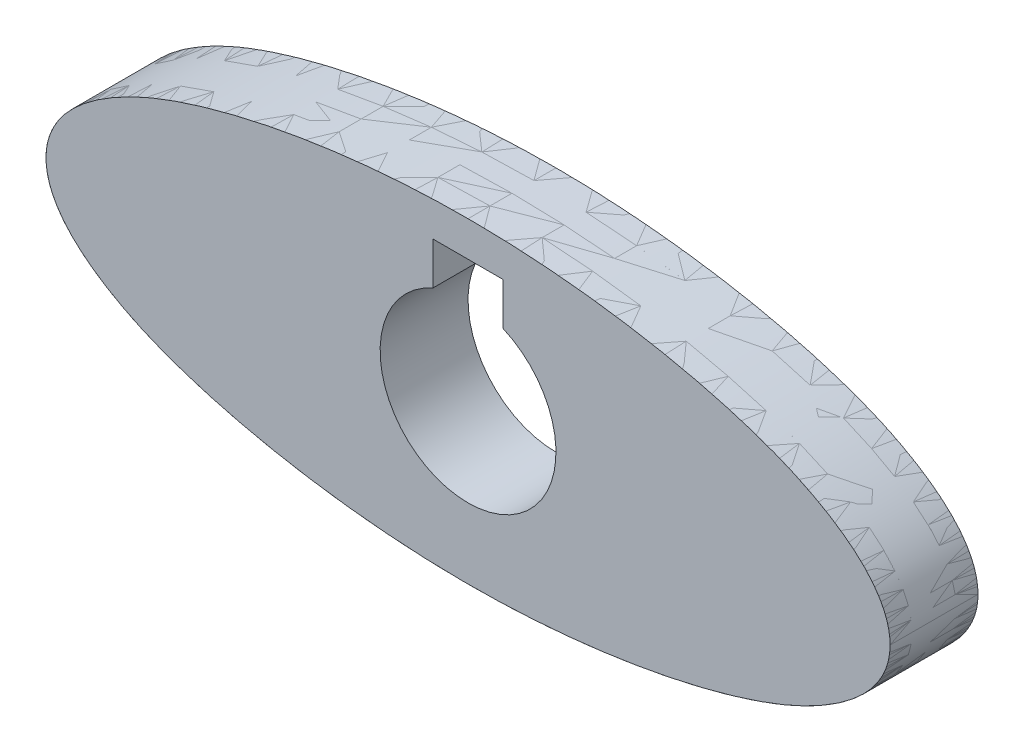
SolidWorks part; units mm, degrees
ref_plane "Alzado" through (0, 0, 0) normal (0, 0, 1) x (1, 0, 0)
ref_plane "Planta" through (0, 0, 0) normal (0, 1, 0) x (1, 0, 0)
ref_plane "Vista lateral" through (0, 0, 0) normal (1, 0, 0) x (0, 0, -1)
ref_plane "Plano1" through (0, 0, 0) normal (0, 0, -1) x (-1, 0, 0)
sketch "Croquis1" plane through (0, 0, 0) normal (0, 0, -1) x (-1, 0, 0)
  circle A0 centre (0, 0) radius 5
  spline S0 degree 3 poles (24, 0) (24, 1.5) (23.04, 3.48) (15.36, 7.32) (8, 9) (-8, 9) (-15.36, 7.32) (-23.04, 3.48) (-24, 1.5) (-24, 0) knots 0 0 0 0 0.25 0.25 0.5 0.5 0.75 0.75 1 1 1 1
  spline S1 degree 3 poles (-24, 0) (-24, -1.5) (-23.04, -3.48) (-15.36, -7.32) (-8, -9) (8, -9) (15.36, -7.32) (23.04, -3.48) (24, -1.5) (24, 0) knots 0 0 0 0 0.25 0.25 0.5 0.5 0.75 0.75 1 1 1 1
extrude "Saliente-Extruir1" add sketch "Croquis1" against normal blind 5
sketch "Croquis2" plane through (0, 0, 5) normal (0, 0, 1) x (1, 0, 0)
  spline S0 degree 3 poles (2832.0202, -1053.5368) (-359.2346, 53.9786) (68.6348, 19.3174) (15.36, -7.32) (8, -9) (-8, -9) (-15.36, -7.32) (-68.6347, 19.3174) (359.2335, 53.9785) (-2832.0071, -1053.5323) knots -2.96841 -2.96841 -2.96841 -2.96841 0.25 0.25 0.5 0.5 0.75 0.75 3.968406 3.968406 3.968406 3.968406 only from (24, 0) to (-24, 0) construction
  spline S1 degree 3 poles (-2832.0202, 1053.5368) (359.2346, -53.9786) (-68.6348, -19.3174) (-15.36, 7.32) (-8, 9) (8, 9) (15.36, 7.32) (68.6347, -19.3174) (-359.2335, -53.9785) (2832.0071, 1053.5323) knots -2.96841 -2.96841 -2.96841 -2.96841 0.25 0.25 0.5 0.5 0.75 0.75 3.968406 3.968406 3.968406 3.968406 only from (-24, 0) to (24, 0) construction
  spline S2 degree 3 poles (24, 0) (24, -1.5) (23.04, -3.48) (15.36, -7.32) (8, -9) (-8, -9) (-15.36, -7.32) (-23.04, -3.48) (-24, -1.5) (-24, 0) knots 0 0 0 0 0.25 0.25 0.5 0.5 0.75 0.75 1 1 1 1
  spline S3 degree 3 poles (-24, 0) (-24, 1.5) (-23.04, 3.48) (-15.36, 7.32) (-8, 9) (8, 9) (15.36, 7.32) (23.04, 3.48) (24, 1.5) (24, 0) knots 0 0 0 0 0.25 0.25 0.5 0.5 0.75 0.75 1 1 1 1
surface "Superficie-Extruir1" sketch "Croquis2" parameters "D1"=5
sketch "Croquis3" plane through (0, 0, 5) normal (0, 0, 1) x (1, 0, 0)
  line L2 (-2, 4.5826) -> (-2, 7)
  line L3 (-2, 7) -> (2, 7)
  line L4 (2, 4.5826) -> (2, 7)
  circle A0 centre (0, 0) radius 5 construction
  arc A1 (2, 4.5826) -> (-2, 4.5826) centre (0, 0) ccw
  point P4 (0, 7)
  dimension "D1" = 7
  dimension "D2" = 4
extrude "Cortar-Extruir1" cut sketch "Croquis3" against normal through all
